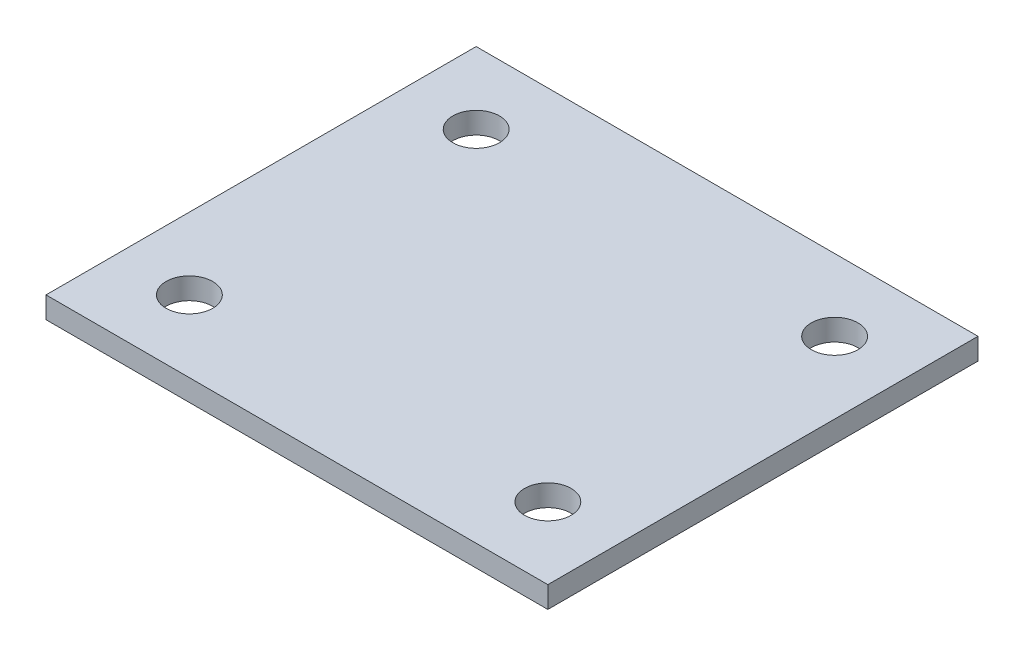
SolidWorks part; units mm, degrees
material "1.0553 (S355J0)"
ref_plane "Płaszczyzna przednia" through (0, 0, 0) normal (0, 0, 1) x (1, 0, 0)
ref_plane "Płaszczyzna górna" through (0, 0, 0) normal (0, 1, 0) x (1, 0, 0)
ref_plane "Płaszczyzna prawa" through (0, 0, 0) normal (1, 0, 0) x (0, 0, -1)
sketch "Szkic1" plane through (0, 0, 0) normal (0, 1, 0) x (1, 0, 0)
  line L0 (10, 10) -> (60, 10) construction
  line L1 (0, 0) -> (70, 0)
  line L2 (0, 0) -> (0, 60)
  line L3 (0, 60) -> (70, 60)
  line L4 (70, 0) -> (70, 60)
  line L5 (10, 50) -> (10, 10) construction
  circle A0 centre (10, 10) radius 3.25
  circle A1 centre (60, 10) radius 3.25
  circle A2 centre (60, 50) radius 3.25
  circle A3 centre (10, 50) radius 3.25
  point P13 (35, 10)
  point P14 (35, 0)
  point P15 (10, 30)
  point P16 (0, 30)
  dimension "D3" = 6.5
  dimension "D1" = 70
  dimension "D2" = 60
  dimension "D4" = 50
  dimension "D6" = 40
extrude "Dodanie-wyciągnięcie1" add sketch "Szkic1" along normal blind 3
